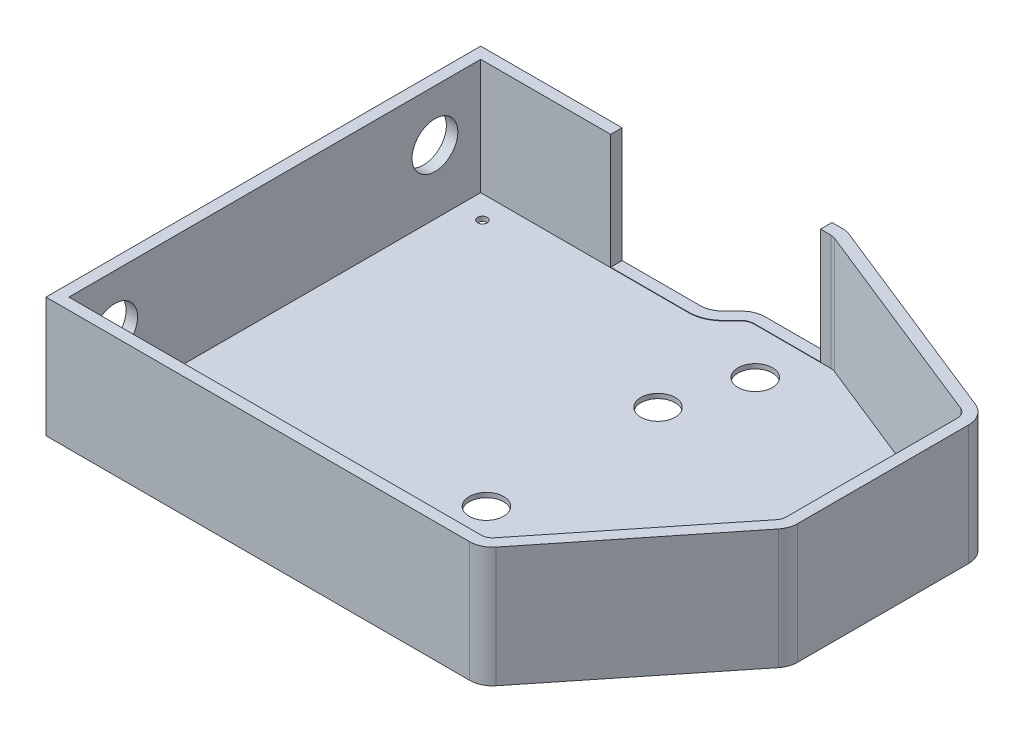
SolidWorks part; units mm, degrees
material "ABS"
ref_plane "Plano frontal" through (0, 0, 0) normal (0, 0, 1) x (1, 0, 0)
ref_plane "Plano superior" through (0, 0, 0) normal (0, 1, 0) x (1, 0, 0)
ref_plane "Plano direito" through (0, 0, 0) normal (1, 0, 0) x (0, 0, -1)
sketch "Esboço1" plane through (0, 2000, 0) normal (0, -1, 0) x (1, 0, 0)
  line L0 (26.1917, -104.7254) -> (63.2305, -104.7254)
  line L2 (64.7922, -105.476) -> (75.7535, -119.1776)
  line L3 (76.1917, -120.427) -> (76.1917, -135.3714)
  line L4 (74.9345, -137.2283) -> (56.5494, -144.5824)
  line L5 (55.8066, -144.7254) -> (49.0202, -144.7254)
  line L8 (47.606, -144.1396) -> (46.7775, -143.3112)
  line L11 (45.3633, -142.7254) -> (26.1917, -142.7254)
  line L12 (26.1917, -142.7254) -> (26.1917, -104.7254)
  line L13 (49.0202, -144.7254) -> (48.5054, -144.658)
  line L14 (48.5054, -144.658) -> (48.0174, -144.4559)
  line L15 (48.0174, -144.4559) -> (47.606, -144.1396)
  line L16 (48.267, -143.3865) -> (47.4846, -142.6041)
  line L17 (48.5221, -143.5826) -> (48.267, -143.3865)
  line L18 (48.7661, -143.6836) -> (48.5221, -143.5826)
  line L19 (49.0853, -143.7254) -> (48.7661, -143.6836)
  line L20 (55.8066, -143.7254) -> (49.0853, -143.7254)
  line L21 (74.5631, -136.2998) -> (56.178, -143.6539)
  line L22 (75.1917, -120.427) -> (75.1917, -135.3714)
  line L23 (64.0114, -106.1007) -> (74.9726, -119.8023)
  line L24 (27.1917, -105.7254) -> (63.2305, -105.7254)
  line L25 (27.1917, -141.7254) -> (27.1917, -105.7254)
  line L26 (45.3633, -141.7254) -> (27.1917, -141.7254)
  arc A0 (75.7535, -119.1776) -> (76.1917, -120.427) centre (74.1917, -120.427) cw
  arc A1 (76.1917, -135.3714) -> (74.9345, -137.2283) centre (74.1917, -135.3714) cw
  arc A2 (56.5494, -144.5824) -> (55.8066, -144.7254) centre (55.8066, -142.7254) cw
  arc A5 (63.2305, -104.7254) -> (64.7922, -105.476) centre (63.2305, -106.7254) cw
  arc A6 (47.606, -144.1396) -> (49.0202, -144.7254) centre (49.0202, -142.7254) ccw construction
  arc A7 (45.3633, -142.7254) -> (46.7775, -143.3112) centre (45.3633, -144.7254) cw
  arc A8 (45.3633, -141.7254) -> (47.4846, -142.6041) centre (45.3633, -144.7254) cw
  arc A9 (56.178, -143.6539) -> (55.8066, -143.7254) centre (55.8066, -142.7254) cw
  arc A10 (75.1917, -135.3714) -> (74.5631, -136.2998) centre (74.1917, -135.3714) cw
  arc A11 (74.9726, -119.8023) -> (75.1917, -120.427) centre (74.1917, -120.427) cw
  arc A12 (63.2305, -105.7254) -> (64.0114, -106.1007) centre (63.2305, -106.7254) cw
  dimension "D1" = 37.0388
  dimension "D2" = 17.5466
  dimension "D3" = 14.9444
  dimension "D4" = 19.8014
  dimension "D5" = 6.7864
  dimension "D6" = 19.1716
  dimension "D7" = 38
  dimension "D8" = 1
sketch "Esboço3" plane through (0, 2000, 0) normal (0, -1, 0) x (1, 0, 0)
extrude "Ressalto-extrusão1" add sketch "Esboço1" along normal blind 10.5
sketch "Esboço5" plane through (0, 1989.5, 0) normal (0, -1, 0) x (1, 0, 0)
  line L0 (27.1917, -105.7254) -> (63.2305, -105.7254)
  line L2 (64.0114, -106.1007) -> (74.9726, -119.8023)
  line L4 (75.1917, -120.427) -> (75.1917, -135.3714)
  line L5 (75.1917, -135.3714) -> (75.1917, -120.427) construction
  line L8 (55.8066, -143.7254) -> (49.0853, -143.7254)
  line L11 (45.3633, -141.7254) -> (27.1917, -141.7254)
  line L12 (27.1917, -141.7254) -> (27.1917, -105.7254)
  line L13 (74.5631, -136.2998) -> (56.178, -143.6539)
  line L14 (47.4846, -142.6041) -> (48.267, -143.3865)
  arc A0 (74.5631, -136.2998) -> (75.1917, -135.3714) centre (74.1917, -135.3714) ccw construction
  arc A1 (63.2305, -105.7254) -> (64.0114, -106.1007) centre (63.2305, -106.7254) cw
  arc A2 (74.9726, -119.8023) -> (75.1917, -120.427) centre (74.1917, -120.427) cw
  arc A3 (75.1917, -135.3714) -> (74.5631, -136.2998) centre (74.1917, -135.3714) cw
  arc A4 (56.178, -143.6539) -> (55.8066, -143.7254) centre (55.8066, -142.7254) cw
  arc A5 (49.0853, -143.7254) -> (48.267, -143.3865) centre (49.0853, -142.5681) cw
  arc A6 (45.3633, -141.7254) -> (47.4846, -142.6041) centre (45.3633, -144.7254) cw
extrude "Ressalto-extrusão2" add sketch "Esboço5" against normal blind 0.4055
sketch "Esboço6" plane through (0, 1989.5, 0) normal (0, -1, 0) x (1, 0, 0)
  circle A0 centre (51.1917, -118.2254) radius 1.5
  circle A1 centre (51.1917, -133.2254) radius 1.5
  circle A2 centre (72.1917, -130.7254) radius 1.5
  circle A3 centre (53.1917, -139.7254) radius 1.5
  circle A4 centre (28.8996, -108.5999) radius 0.4399
  circle A5 centre (29.3394, -139.7254) radius 0.42
sketch "Esboço7" plane through (26.1917, 0, 0) normal (-1, 0, 0) x (0, 0, 1)
  circle A0 centre (-137.7254, 1995.5) radius 2
  circle A1 centre (-109.7254, 1995.5) radius 2
extrude "Corte-extrusão1" cut sketch "Esboço6" against normal blind 10
extrude "Corte-extrusão2" cut sketch "Esboço7" against normal blind 10
sketch "Esboço8" plane through (0, 0, -144.7254) normal (0, 0, -1) x (-1, 0, 0)
  line L1 (-54.8987, 2000.0455) -> (-38.5536, 2000.0455)
  line L2 (-54.8987, 2000.0455) -> (-54.8987, 1989.9448)
  line L3 (-54.8987, 1989.9448) -> (-38.5536, 1989.9448)
  line L4 (-38.5536, 2000.0455) -> (-38.5536, 1989.9448)
  point P4 (0, 0)
extrude "Corte-extrusão3" cut sketch "Esboço8" against normal blind 6
